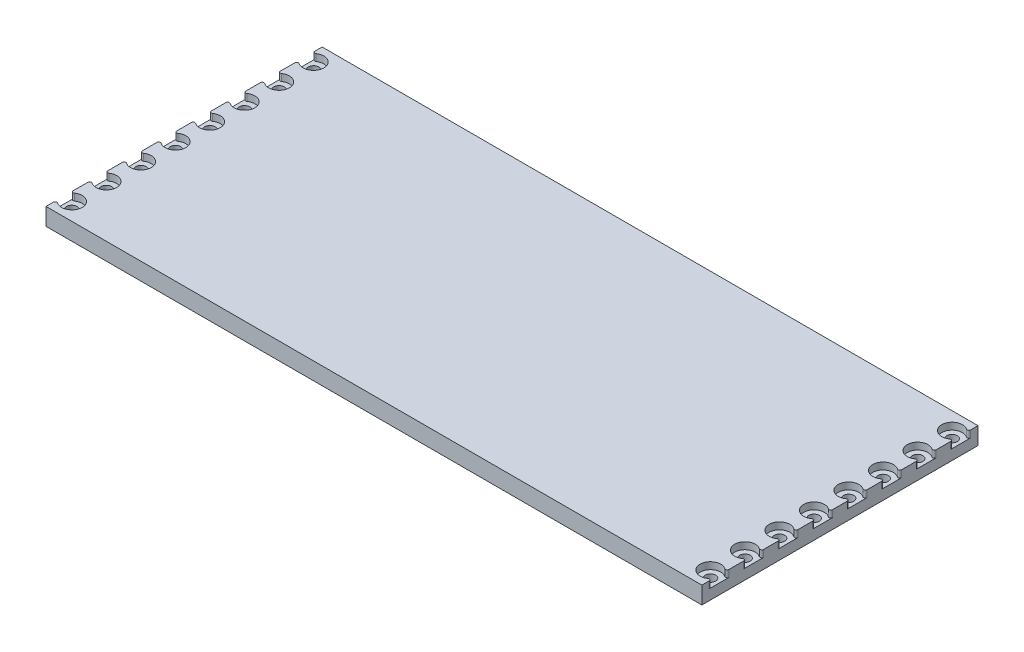
SolidWorks part; units mm, degrees
ref_plane "Front Plane" through (0, 0, 0) normal (0, 0, 1) x (1, 0, 0)
ref_plane "Top Plane" through (0, 0, 0) normal (0, 1, 0) x (1, 0, 0)
ref_plane "Right Plane" through (0, 0, 0) normal (1, 0, 0) x (0, 0, -1)
sketch "Sketch3" plane through (0, 0, 0) normal (0, 1, 0) x (1, 0, 0)
  line L1 (-95, -40) -> (95, -40)
  line L2 (-95, -40) -> (-95, 40)
  line L3 (-95, 40) -> (95, 40)
  line L4 (95, -40) -> (95, 40)
  line L5 (-95, -40) -> (95, 40) construction
  line L6 (-95, 40) -> (95, -40) construction
  point P0 (0, 0)
  dimension "D1" = 80
  dimension "D2" = 190
extrude "Boss-Extrude1" add sketch "Sketch3" along normal blind 5
sketch "Sketch4" plane through (0, 5, 0) normal (0, 1, 0) x (1, 0, 0)
  line L0 (-92.5, 40) -> (-92.5, -40) construction
  line L1 (92.5, 40) -> (92.5, -40) construction
  line L2 (0, 0) -> (0, 40) construction
  line L4 (95, -40) -> (95, 40)
  line L5 (95, 40) -> (-95, 40)
  line L6 (-95, 40) -> (-95, -40)
  line L7 (-95, -40) -> (95, -40)
  line L8 (95, -40) -> (95, 40)
  line L9 (95, 40) -> (-95, 40)
  line L10 (-95, 40) -> (-95, -40)
  line L11 (-95, -40) -> (95, -40)
  circle A0 centre (-92.5, 35) radius 1.5
  circle A1 centre (-92.5, 25) radius 1.5
  circle A2 centre (-92.5, 15) radius 1.5
  circle A3 centre (-92.5, 5) radius 1.5
  circle A4 centre (-92.5, -5) radius 1.5
  circle A5 centre (-92.5, -15) radius 1.5
  circle A6 centre (-92.5, -25) radius 1.5
  circle A7 centre (-92.5, -35) radius 1.5
  circle A8 centre (92.5, -35) radius 1.5
  circle A9 centre (92.5, -25) radius 1.5
  circle A10 centre (92.5, -15) radius 1.5
  circle A11 centre (92.5, -5) radius 1.5
  circle A12 centre (92.5, 5) radius 1.5
  circle A13 centre (92.5, 15) radius 1.5
  circle A14 centre (92.5, 35) radius 1.5
  circle A15 centre (92.5, 25) radius 1.5
  dimension "D4" = 3
  dimension "D5" = 5
  dimension "D2" = 2.5
  dimension "D3" = 2.5
  dimension "D6" = 8
  dimension "D7" = 5
  dimension "D1" = 0
extrude "Cut-Extrude1" cut sketch "Sketch4" against normal blind 5 contours A0 | A1 | A2 | A3 | A4 | A5 | A6 | A7 | A14 | A15 | A13 | A12 | A11 | A10 | A9 | A8
sketch "Sketch5" plane through (0, 5, 0) normal (0, 1, 0) x (1, 0, 0)
  line L0 (-95, -40) -> (95, -40) construction
  circle A0 centre (92.5, 35) radius 1.5 construction
  circle A1 centre (-92.5, 35) radius 1.5 construction
  circle A2 centre (92.5, 35) radius 1.5
  circle A3 centre (-92.5, 35) radius 1.5
  circle A4 centre (-92.5, 35) radius 3
  circle A5 centre (92.5, 35) radius 3
  circle A6 centre (-92.5, 25) radius 3
  circle A7 centre (92.5, 25) radius 3
  circle A8 centre (-92.5, 15) radius 3
  circle A9 centre (92.5, 15) radius 3
  circle A10 centre (-92.5, 5) radius 3
  circle A11 centre (92.5, 5) radius 3
  circle A12 centre (-92.5, -5) radius 3
  circle A13 centre (92.5, -5) radius 3
  circle A14 centre (-92.5, -15) radius 3
  circle A15 centre (92.5, -15) radius 3
  circle A16 centre (-92.5, -25) radius 3
  circle A17 centre (92.5, -25) radius 3
  circle A18 centre (-92.5, -35) radius 3
  circle A19 centre (92.5, -35) radius 3
  dimension "D1" = 6
  dimension "D2" = 6
  dimension "D4" = 5
  dimension "D3" = 8
extrude "Cut-Extrude2" cut sketch "Sketch5" against normal blind 2
fillet "Fillet1" radius 0.5 32 edges at (95, 4, 33.3417) (95, 4, 36.6583) (95, 4, 23.3417) (95, 4, 26.6583) (95, 4, 13.3417) (95, 4, 16.6583) (95, 4, 3.3417) (95, 4, 6.6583) (95, 4, -6.6583) (95, 4, -3.3417) (95, 4, -13.3417) (95, 4, -16.6583) (95, 4, -26.6583) (95, 4, -23.3417) (95, 4, -36.6583) (95, 4, -33.3417) (-95, 4, 6.6583) (-95, 4, 3.3417) (-95, 4, 16.6583) (-95, 4, 13.3417) (-95, 4, 26.6583) (-95, 4, 23.3417) (-95, 4, 36.6583) (-95, 4, 33.3417) (-95, 4, -6.6583) (-95, 4, -3.3417) (-95, 4, -13.3417) (-95, 4, -16.6583) (-95, 4, -23.3417) (-95, 4, -26.6583) (-95, 4, -33.3417) (-95, 4, -36.6583)
